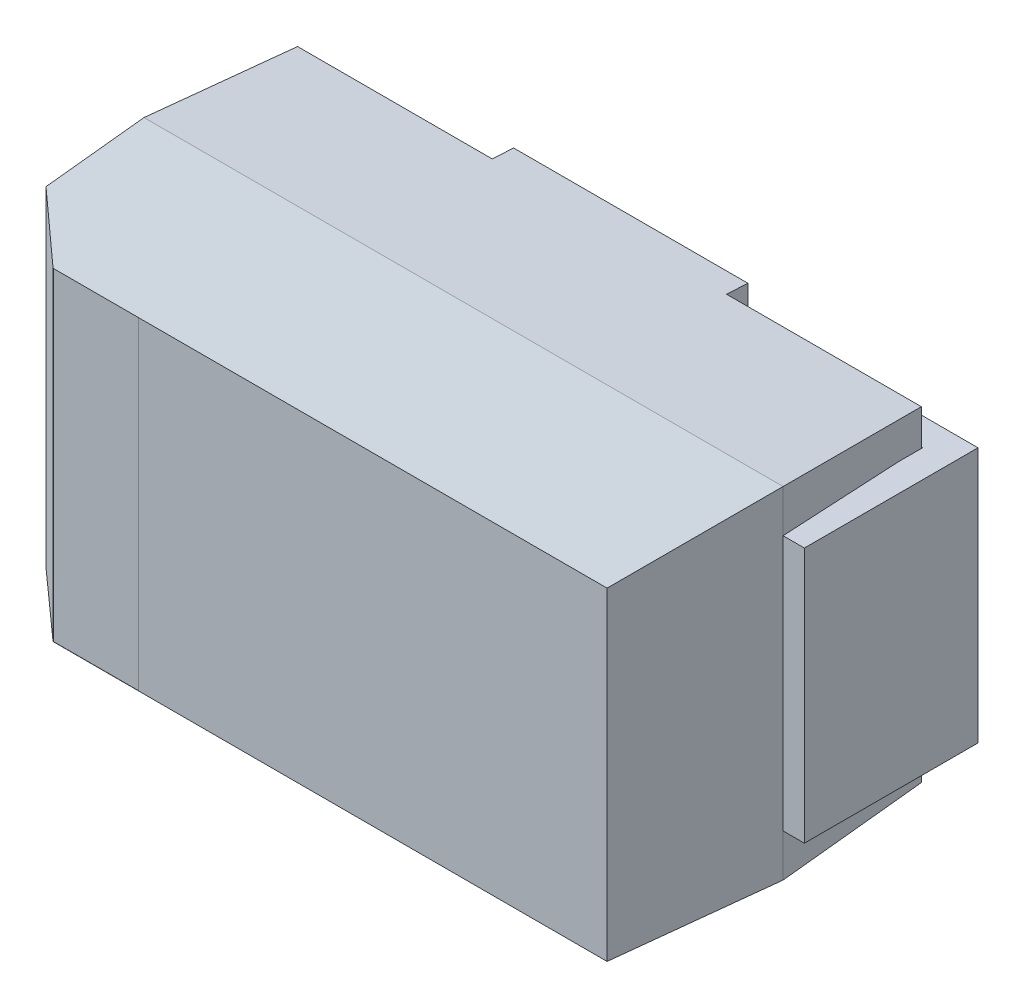
SolidWorks part; units mm, degrees
ref_plane "Plan de face" through (0, 0, 0) normal (0, 0, 1) x (1, 0, 0)
ref_plane "Plan de dessus" through (0, 0, 0) normal (0, 1, 0) x (1, 0, 0)
ref_plane "Plan de droite" through (0, 0, 0) normal (1, 0, 0) x (0, 0, -1)
ref_plane "Plane1" through (0, 0, 0.815) normal (0, 0, 1) x (1, 0, 0)
sketch "Sketch1" plane through (0, 0, 0.815) normal (0, 0, 1) x (1, 0, 0)
  line L1 (-1.5, 0.8) -> (1.5, 0.8)
  line L2 (-1.5, 0.8) -> (-1.5, -0.8)
  line L3 (-1.5, -0.8) -> (1.5, -0.8)
  line L4 (1.5, 0.8) -> (1.5, -0.8)
  line L5 (-1.5, 0.8) -> (1.5, -0.8) construction
  line L6 (-1.5, -0.8) -> (1.5, 0.8) construction
  point P0 (0, 0)
  dimension "D1" = 1.6
  dimension "D2" = 3
extrude "Boss-Extrude1" add sketch "Sketch1" along normal blind 0.785
draft "Draft2" type of draft neutral plane draft angle 3 neutral plane "Plane1" faces to draft 4 face at (-1.5, 0, 1.2075) face at (0, 0.8, 1.2075) face at (1.5, 0, 1.2075) face at (0, -0.8, 1.2075) neutral plane through (0, 0, 0.815) neutral plane normal (0, 0, 1) parameters "D1"=3
mirror "Mirror2" about plane through (0, 0, 0.815) normal (0, 0, 1) of "Draft2", "Boss-Extrude1"
chamfer "Chamfer1" distance 0.3 angle 45 1 edges at (-1.4589, 0, 1.6)
sketch "Sketch2" plane through (0, 0, 0.03) normal (0, 0, -1) x (-1, 0, 0)
  line L1 (-1.9006, 0.8344) -> (-0.55, 0.8344)
  line L2 (-1.9006, 0.8344) -> (-1.9006, -0.8905)
  line L3 (-1.9006, -0.8905) -> (-0.55, -0.8905)
  line L4 (-0.55, 0.8344) -> (-0.55, -0.8905)
  dimension "D1" = 0.55
extrude "Cut-Extrude1" cut sketch "Sketch2" against normal blind 0.1
mirror "Mirror3" about plane through (0, 0, 0) normal (1, 0, 0) of "Cut-Extrude1"
sketch "Sketch3" plane through (0, 0, 0) normal (0, 1, 0) x (1, 0, 0)
  line L0 (0.6, -0.13) -> (0.6, 0)
  line L2 (0.6, 0) -> (1.6, 0)
  line L3 (1.6, 0) -> (1.6, -0.815)
  line L4 (-0.88, -0.815) -> (0.88, -0.815) construction
  line L5 (1.6, -0.815) -> (1.47, -0.815)
  line L6 (1.47, -0.815) -> (1.47, -0.13)
  line L7 (1.47, -0.13) -> (0.6, -0.13)
  point P2 (0, 0)
  point P3 (0, 0)
  point P9 (0, 0)
  dimension "D1" = 0.13
  dimension "D2" = 0.13
  dimension "D3" = 0.6
  dimension "D4" = 1.6
extrude "Boss-Extrude3" add sketch "Sketch3" along normal mid plane 1.2
mirror "Mirror4" about plane through (0, 0, 0) normal (1, 0, 0) of "Boss-Extrude3"
sketch "Sketch4" plane through (0, 0, 1.6) normal (0, 0, 1) x (1, 0, 0)
  line L0 (-1.1418, -0.7589) -> (1.4589, -0.7589) construction
  line L1 (-0.7418, 0.7589) -> (-1.1418, 0.7589)
  line L2 (-0.7418, 0.7589) -> (-0.7418, -0.7589)
  line L3 (-0.7418, -0.7589) -> (-1.1418, -0.7589)
  line L4 (-1.1418, 0.7589) -> (-1.1418, -0.7589)
  line L5 (-1.1418, 0.7589) -> (-1.1418, -0.7589) construction
  dimension "D1" = 0.4
extrude "Cut-Extrude2" cut sketch "Sketch4" against normal blind 0.001
